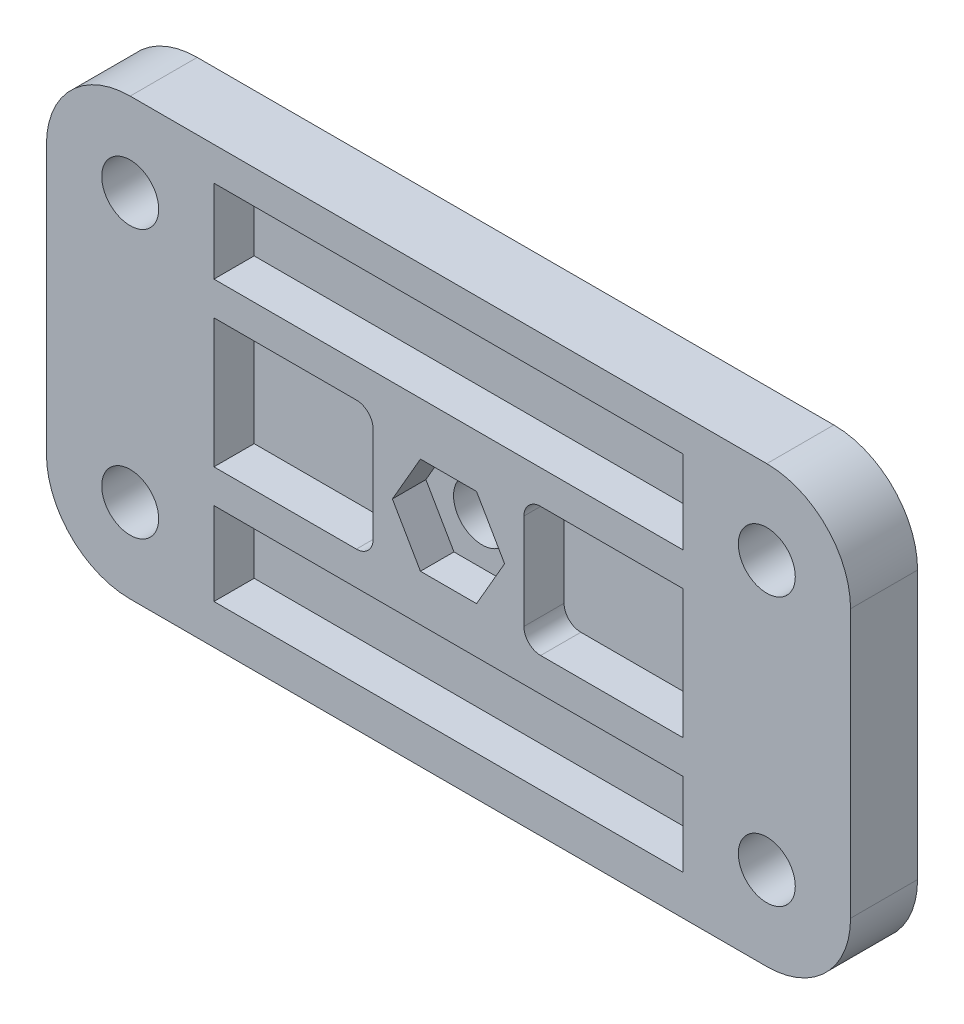
SolidWorks part; units mm, degrees
ref_plane "Front Plane" through (0, 0, 0) normal (0, 0, 1) x (1, 0, 0)
ref_plane "Top Plane" through (0, 0, 0) normal (0, 1, 0) x (1, 0, 0)
ref_plane "Right Plane" through (0, 0, 0) normal (1, 0, 0) x (0, 0, -1)
sketch "Sketch1" plane through (0, 0, 0) normal (0, 0, 1) x (1, 0, 0)
  line L0 (-19, 0) -> (19, 0) construction
  line L1 (-19, -8) -> (19, -8) construction
  line L2 (-19, -8) -> (-19, 8) construction
  line L3 (-19, 8) -> (19, 8) construction
  line L4 (19, -8) -> (19, 8) construction
  line L6 (-19, -13) -> (19, -13)
  line L7 (-24, -8) -> (-24, 8)
  line L8 (-19, 13) -> (19, 13)
  line L9 (24, -8) -> (24, 8)
  circle A0 centre (0, 0) radius 1.7
  circle A1 centre (19, 8) radius 1.7
  circle A2 centre (19, -8) radius 1.7
  circle A3 centre (-19, -8) radius 1.7
  circle A4 centre (-19, 8) radius 1.7
  arc A5 (24, -8) -> (19, -13) centre (19, -8) cw
  arc A6 (-19, -13) -> (-24, -8) centre (-19, -8) cw
  arc A7 (-24, 8) -> (-19, 13) centre (-19, 8) cw
  arc A8 (19, 13) -> (24, 8) centre (19, 8) cw
  dimension "D1" = 3.4
  dimension "D4" = 5
  dimension "D2" = 38
  dimension "D3" = 16
extrude "Boss-Extrude1" add sketch "Sketch1" along normal blind 4
sketch "Sketch2" plane through (0, 0, 4) normal (0, 0, 1) x (1, 0, 0)
  line L1 (3.3486, 0) -> (1.6743, 2.9)
  line L2 (1.6743, 2.9) -> (-1.6743, 2.9)
  line L3 (-1.6743, 2.9) -> (-3.3486, 0)
  line L4 (-3.3486, 0) -> (-1.6743, -2.9)
  line L5 (-1.6743, -2.9) -> (1.6743, -2.9)
  line L6 (1.6743, -2.9) -> (3.3486, 0)
  circle A0 centre (0, 0) radius 2.9 construction
  circle A1 centre (0, 0) radius 1.7 construction
  dimension "D1" = 5.8
extrude "Cut-Extrude1" cut sketch "Sketch2" against normal blind 2
sketch "Sketch3" plane through (0, 0, 4) normal (0, 0, 1) x (1, 0, 0)
  line L0 (24, -8) -> (24, 8) construction
  line L1 (-14, 6.0393) -> (14, 6.0393)
  line L2 (-14, 6.0393) -> (-14, 11)
  line L3 (-14, 11) -> (14, 11)
  line L4 (14, 6.0393) -> (14, 11)
  line L5 (-24, 8) -> (-24, -8) construction
  line L6 (19, 13) -> (-19, 13) construction
  line L7 (-14, 4.0393) -> (-4.5, 4.0393)
  line L8 (-14, 4.0393) -> (-14, -3.6667)
  line L9 (-14, -3.6667) -> (-4.5, -3.6667)
  line L10 (-4.5, 4.0393) -> (-4.5, -3.6667)
  line L11 (4.5, 4.0393) -> (14, 4.0393)
  line L12 (4.5, 4.0393) -> (4.5, -3.6667)
  line L13 (4.5, -3.6667) -> (14, -3.6667)
  line L14 (14, 4.0393) -> (14, -3.6667)
  line L15 (-14, -5.6667) -> (14, -5.6667)
  line L16 (-14, -5.6667) -> (-14, -10.6274)
  line L17 (-14, -10.6274) -> (14, -10.6274)
  line L18 (14, -5.6667) -> (14, -10.6274)
  line L19 (-14, 6.0393) -> (-14, 4.0393) construction
  line L20 (-14, -3.6667) -> (-14, -5.6667) construction
  line L21 (-14, 11) -> (-14, 13) construction
  dimension "D1" = 10
  dimension "D2" = 10
  dimension "D3" = 2
  dimension "D4" = 9
extrude "Cut-Extrude2" cut sketch "Sketch3" against normal blind 2.4
fillet "Fillet1" radius 1 4 edges at (4.5, -3.6667, 2.8) (4.5, 4.0393, 2.8) (-4.5, -3.6667, 2.8) (-4.5, 4.0393, 2.8)
sketch "Sketch4" plane through (0, 0, 4) normal (0, 0, 1) x (1, 0, 0)
  line L0 (-24, 8) -> (-24, -8) construction
  line L1 (-24, -2.3038) -> (-14, -2.3038)
  line L2 (-24, -2.3038) -> (-24, 2.1962)
  line L3 (-24, 2.1962) -> (-14, 2.1962)
  line L4 (-14, -2.3038) -> (-14, 2.1962)
  line L5 (-14, 4.0393) -> (-14, -3.6667) construction
  line L6 (-24, -0.0538) -> (0, 0) construction
  dimension "D1" = 4.5
extrude "Boss-Extrude2" [suppressed] add sketch "Sketch4" along normal blind 0.3
